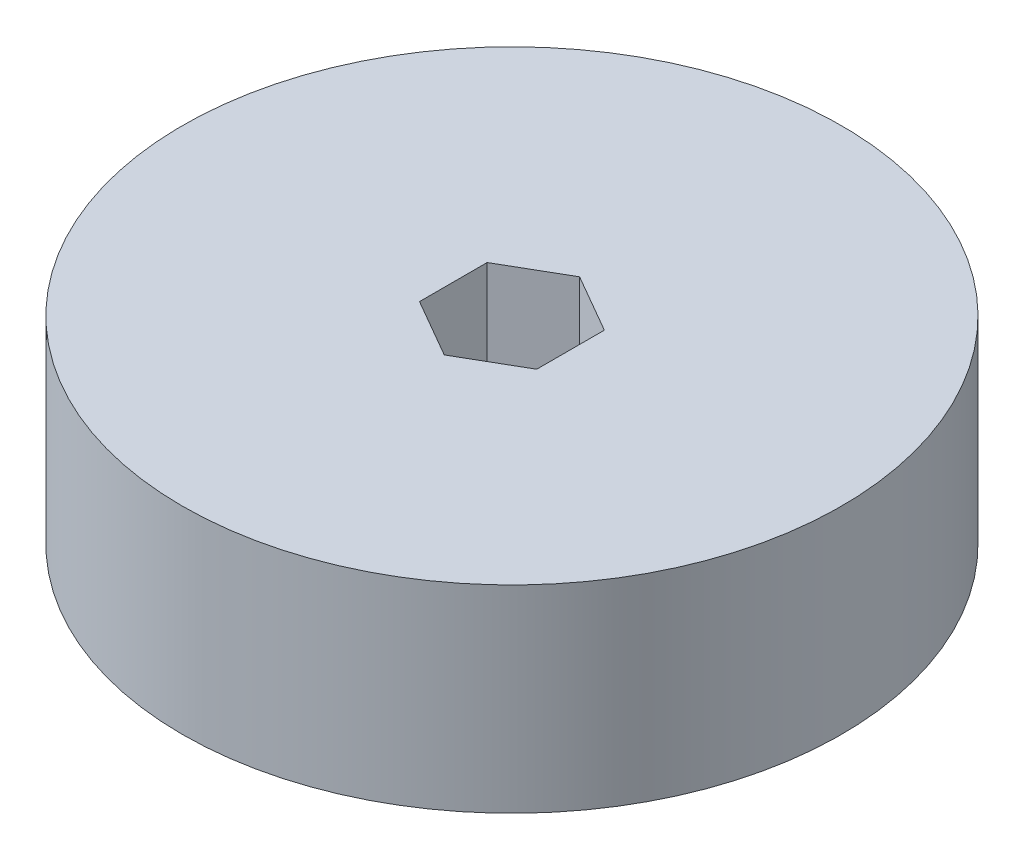
SolidWorks part; units mm, degrees
ref_plane "Front Plane" through (0, 0, 0) normal (0, 0, 1) x (1, 0, 0)
ref_plane "Top Plane" through (0, 0, 0) normal (0, 1, 0) x (1, 0, 0)
ref_plane "Right Plane" through (0, 0, 0) normal (1, 0, 0) x (0, 0, -1)
sketch "Sketch1" plane through (0, 0, 0) normal (0, 1, 0) x (1, 0, 0)
  circle A0 centre (0, 0) radius 25
  dimension "D1" = 50
extrude "Boss-Extrude1" add sketch "Sketch1" along normal blind 15 contours A0
sketch "Sketch7" plane through (0, 15, 0) normal (0, 1, 0) x (1, 0, 0)
  line L0 (0, 5.1326) -> (-4.445, 2.5663)
  line L1 (-4.445, 2.5663) -> (-4.445, -2.5663)
  line L2 (-4.445, -2.5663) -> (0, -5.1326)
  line L3 (0, -5.1326) -> (4.445, -2.5663)
  line L4 (4.445, -2.5663) -> (4.445, 2.5663)
  line L5 (4.445, 2.5663) -> (0, 5.1326)
  line L6 (0, 25) -> (0, -25) construction
  line L7 (-25, 0) -> (25, 0) construction
  line L8 (0, 5.1326) -> (0, -5.1326) construction
  line L9 (-4.445, 0) -> (4.445, 0) construction
  line L10 (4.445, 2.5663) -> (-4.445, -2.5663) construction
  line L11 (-4.445, 2.5663) -> (4.445, -2.5663) construction
  circle A0 centre (0, 0) radius 25 construction
  point P15 (0, 0)
  point P17 (0, 0)
extrude "Cut-Extrude2" cut sketch "Sketch7" against normal up to next
sketch "Sketch8" plane through (0, 0, 0) normal (0, -1, 0) x (1, 0, 0)
  line L4 (0, 25) -> (0, -25) construction
  line L5 (-25, 0) -> (25, 0) construction
  circle A4 centre (0, 0) radius 25 construction
  arc A19 (2.8678, 6.2766) -> (8.1035, 4.0243) centre (-3.6427, -16.0687) cw
  arc A20 (8.1035, 4.0243) -> (17.4455, 2.5243) centre (-5.206, -108.7086) cw
  arc A21 (17.4455, 2.5243) -> (21, -0.4757) centre (17.8847, -0.5611) cw
  arc A22 (17.4455, -3.4757) -> (21, -0.4757) centre (17.8847, -0.3904) ccw
  arc A23 (2.8678, -7.2281) -> (8.1035, -4.9757) centre (-3.6427, 15.1172) ccw
  arc A24 (8.1035, -4.9757) -> (17.4455, -3.4757) centre (-5.206, 107.7571) ccw
  arc A25 (2.8678, 6.2766) -> (-2.8678, 6.2766) centre (0, 0) ccw
  arc A26 (-2.8678, -7.2281) -> (2.8678, -7.2281) centre (0, -0.9515) ccw
  arc A27 (-2.8678, 6.2766) -> (-8.1035, 4.0243) centre (3.6427, -16.0687) ccw
  arc A28 (-8.1035, 4.0243) -> (-17.4455, 2.5243) centre (5.206, -108.7086) ccw
  arc A29 (-17.4455, 2.5243) -> (-21, -0.4757) centre (-17.8847, -0.5611) ccw
  arc A30 (-17.4455, -3.4757) -> (-21, -0.4757) centre (-17.8847, -0.3904) cw
  arc A31 (-8.1035, -4.9757) -> (-17.4455, -3.4757) centre (5.206, 107.7571) cw
  arc A32 (-2.8678, -7.2281) -> (-8.1035, -4.9757) centre (3.6427, 15.1172) cw
  point P35 (0, 0)
extrude "Cut-Extrude3" cut sketch "Sketch8" against normal blind 5
